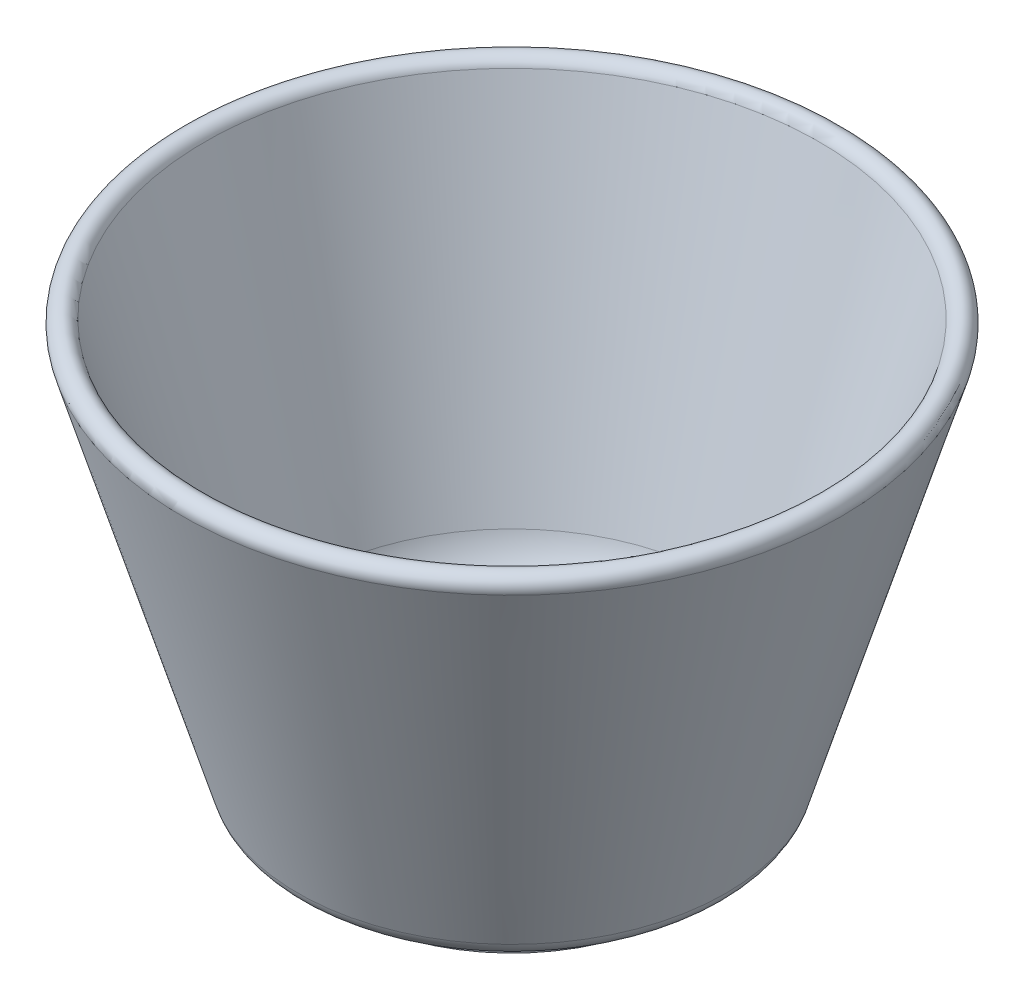
SolidWorks part; units mm, degrees
material "玻璃"
ref_plane "前视基准面" through (0, 0, 0) normal (0, 0, 1) x (1, 0, 0)
ref_plane "上视基准面" through (0, 0, 0) normal (0, 1, 0) x (1, 0, 0)
ref_plane "右视基准面" through (0, 0, 0) normal (1, 0, 0) x (0, 0, -1)
other "Configuration Table"
sketch "草图2" plane through (0, 0, 0) normal (0, 0, 1) x (1, 0, 0)
  line L0 (0, -950.3241) -> (0, 46565.8792) construction
  line L1 (-40, 50) -> (-27.138, 7.1265)
  line L2 (-17.5597, 0) -> (0, 0)
  line L3 (-42.8735, 49.138) -> (-27.8735, -0.862)
  line L4 (-19, -3) -> (0, -3)
  line L5 (-19, -3) -> (-19, -6)
  line L6 (-19, -6) -> (-22, -6)
  line L7 (-22, -6) -> (-22, -3)
  line L8 (-22, -3) -> (-25, -3)
  line L9 (0, -3) -> (0, 0)
  arc A0 (-17.5597, 0) -> (-27.138, 7.1265) centre (-17.5597, 10) cw
  arc A1 (-25, -3) -> (-27.8735, -0.862) centre (-25, 0) cw
  arc A2 (-40, 50) -> (-42.8735, 49.138) centre (-41.4367, 49.569) ccw
  point P8 (-25, 0)
  dimension "D4" = 10
  dimension "D5" = 3
  dimension "D11" = 1.5
  dimension "D1" = 50
  dimension "D2" = 50
  dimension "D3" = 80
  dimension "D6" = 3
  dimension "D7" = 3
  dimension "D8" = 3
  dimension "D9" = 3
  dimension "D10" = 3
revolve "旋转1" add sketch "草图2" angle 360 about L0
fillet "圆角1" radius 2 2 edges at (19, -3, 0) (22, -3, 0)
